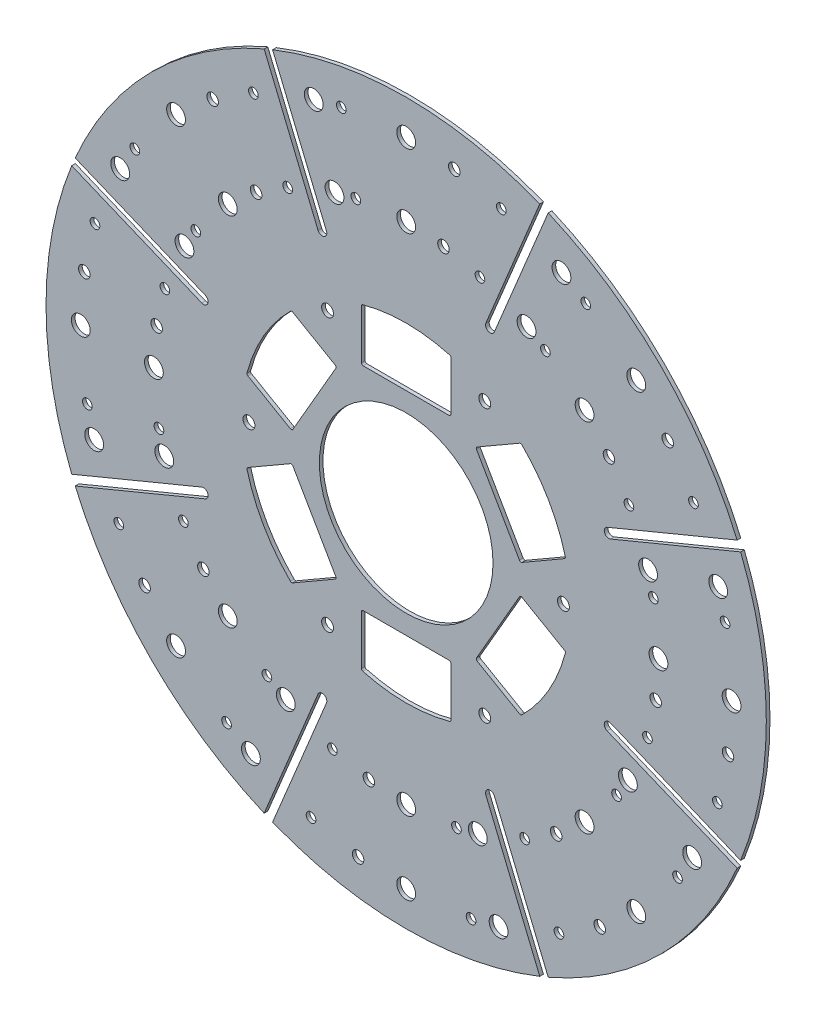
SolidWorks part; units mm, degrees
ref_plane "Plano frontal" through (0, 0, 0) normal (0, 0, 1) x (1, 0, 0)
ref_plane "Plano superior" through (0, 0, 0) normal (0, 1, 0) x (1, 0, 0)
ref_plane "Plano direito" through (0, 0, 0) normal (1, 0, 0) x (0, 0, -1)
sketch "Esboço1" plane through (0, 0, 0) normal (0, 0, 1) x (1, 0, 0)
  circle A0 centre (0, 0) radius 197
  circle A1 centre (0, 0) radius 47.5
  dimension "D1" = 394
  dimension "D2" = 95
extrude "Ressalto-extrusão1" add sketch "Esboço1" along normal blind 2
sketch "Esboço2" plane through (0, 0, 2) normal (0, 0, 1) x (1, 0, 0)
  line L0 (73.0789, 182.961) -> (77.6983, 181.0476)
  line L4 (73.0789, 182.961) -> (43.6023, 111.7982)
  line L5 (77.6983, 181.0476) -> (48.2217, 109.8848)
  line L9 (181.0476, 77.6983) -> (182.961, 73.0789)
  line L10 (181.0476, 77.6983) -> (109.8848, 48.2217)
  line L11 (182.961, 73.0789) -> (111.7982, 43.6023)
  line L15 (182.961, -73.0789) -> (181.0476, -77.6983)
  line L16 (182.961, -73.0789) -> (111.7982, -43.6023)
  line L17 (181.0476, -77.6983) -> (109.8848, -48.2217)
  line L21 (77.6983, -181.0476) -> (73.0789, -182.961)
  line L22 (77.6983, -181.0476) -> (48.2217, -109.8848)
  line L23 (73.0789, -182.961) -> (43.6023, -111.7982)
  line L27 (-73.0789, -182.961) -> (-77.6983, -181.0476)
  line L28 (-73.0789, -182.961) -> (-43.6023, -111.7982)
  line L29 (-77.6983, -181.0476) -> (-48.2217, -109.8848)
  line L33 (-181.0476, -77.6983) -> (-182.961, -73.0789)
  line L34 (-181.0476, -77.6983) -> (-109.8848, -48.2217)
  line L35 (-182.961, -73.0789) -> (-111.7982, -43.6023)
  line L39 (-182.961, 73.0789) -> (-181.0476, 77.6983)
  line L40 (-182.961, 73.0789) -> (-111.7982, 43.6023)
  line L41 (-181.0476, 77.6983) -> (-109.8848, 48.2217)
  line L45 (-77.6983, 181.0476) -> (-73.0789, 182.961)
  line L46 (-77.6983, 181.0476) -> (-48.2217, 109.8848)
  line L47 (-73.0789, 182.961) -> (-43.6023, 111.7982)
  arc A1 (43.6023, 111.7982) -> (48.2217, 109.8848) centre (45.912, 110.8415) ccw
  arc A4 (109.8848, 48.2217) -> (111.7982, 43.6023) centre (110.8415, 45.912) ccw
  arc A6 (111.7982, -43.6023) -> (109.8848, -48.2217) centre (110.8415, -45.912) ccw
  arc A8 (48.2217, -109.8848) -> (43.6023, -111.7982) centre (45.912, -110.8415) ccw
  arc A10 (-43.6023, -111.7982) -> (-48.2217, -109.8848) centre (-45.912, -110.8415) ccw
  arc A12 (-109.8848, -48.2217) -> (-111.7982, -43.6023) centre (-110.8415, -45.912) ccw
  arc A14 (-111.7982, 43.6023) -> (-109.8848, 48.2217) centre (-110.8415, 45.912) ccw
  arc A16 (-48.2217, 109.8848) -> (-43.6023, 111.7982) centre (-45.912, 110.8415) ccw
  point P84 (0, 0)
extrude "Corte-extrusão1" cut sketch "Esboço2" against normal blind 2
sketch "Esboço3" plane through (0, 0, 2) normal (0, 0, 1) x (1, 0, 0)
  line L0 (0, 0) -> (0, 197) construction
  line L1 (0, 0) -> (-35.4875, 174.4266) construction
  line L2 (0, 0) -> (-50.5547, 170.6699) construction
  line L3 (0, 0) -> (26.3101, 176.0448) construction
  line L4 (0, 0) -> (52.0422, 170.2222) construction
  arc A0 (73.0729, 182.9463) -> (-73.0729, 182.9463) centre (0, 0) ccw construction
  circle A1 centre (0, 0) radius 178 construction
  circle A2 centre (0, 0) radius 138 construction
  circle A3 centre (-50.5547, 170.6699) radius 5.15
  circle A4 centre (-39.1941, 132.3171) radius 5.15
  circle A5 centre (-35.4875, 174.4266) radius 2.65
  circle A6 centre (-27.5128, 135.2296) radius 2.65
  circle A7 centre (0, 178) radius 5.15
  circle A8 centre (0, 138) radius 5.15
  circle A9 centre (26.3101, 176.0448) radius 3.15
  circle A10 centre (20.3977, 136.4842) radius 3.15
  circle A11 centre (52.0422, 170.2222) radius 2.65
  circle A12 centre (40.3473, 131.9701) radius 2.65
  circle A13 centre (84.9343, 156.4294) radius 5.15
  circle A14 centre (65.8479, 121.2768) radius 5.15
  circle A15 centre (98.2448, 148.4317) radius 2.65
  circle A16 centre (76.1673, 115.0762) radius 2.65
  circle A17 centre (125.865, 125.865) radius 5.15
  circle A18 centre (97.5807, 97.5807) radius 5.15
  circle A19 centre (143.0865, 105.8785) radius 3.15
  circle A20 centre (110.9322, 82.0855) radius 3.15
  circle A21 centre (157.1647, 83.5659) radius 2.65
  circle A22 centre (121.8468, 64.7871) radius 2.65
  circle A23 centre (170.6699, 50.5547) radius 5.15
  circle A24 centre (132.3171, 39.1941) radius 5.15
  circle A25 centre (174.4266, 35.4875) radius 2.65
  circle A26 centre (135.2296, 27.5128) radius 2.65
  circle A27 centre (178, 0) radius 5.15
  circle A28 centre (138, 0) radius 5.15
  circle A29 centre (176.0448, -26.3101) radius 3.15
  circle A30 centre (136.4842, -20.3977) radius 3.15
  circle A31 centre (170.2222, -52.0422) radius 2.65
  circle A32 centre (131.9701, -40.3473) radius 2.65
  circle A33 centre (156.4294, -84.9343) radius 5.15
  circle A34 centre (121.2768, -65.8479) radius 5.15
  circle A35 centre (148.4317, -98.2448) radius 2.65
  circle A36 centre (115.0762, -76.1673) radius 2.65
  circle A37 centre (125.865, -125.865) radius 5.15
  circle A38 centre (97.5807, -97.5807) radius 5.15
  circle A39 centre (105.8785, -143.0865) radius 3.15
  circle A40 centre (82.0855, -110.9322) radius 3.15
  circle A41 centre (83.5659, -157.1647) radius 2.65
  circle A42 centre (64.7871, -121.8468) radius 2.65
  circle A43 centre (50.5547, -170.6699) radius 5.15
  circle A44 centre (39.1941, -132.3171) radius 5.15
  circle A45 centre (35.4875, -174.4266) radius 2.65
  circle A46 centre (27.5128, -135.2296) radius 2.65
  circle A47 centre (0, -178) radius 5.15
  circle A48 centre (0, -138) radius 5.15
  circle A49 centre (-26.3101, -176.0448) radius 3.15
  circle A50 centre (-20.3977, -136.4842) radius 3.15
  circle A51 centre (-52.0422, -170.2222) radius 2.65
  circle A52 centre (-40.3473, -131.9701) radius 2.65
  circle A53 centre (-84.9343, -156.4294) radius 5.15
  circle A54 centre (-65.8479, -121.2768) radius 5.15
  circle A55 centre (-98.2448, -148.4317) radius 2.65
  circle A56 centre (-76.1673, -115.0762) radius 2.65
  circle A57 centre (-125.865, -125.865) radius 5.15
  circle A58 centre (-97.5807, -97.5807) radius 5.15
  circle A59 centre (-143.0865, -105.8785) radius 3.15
  circle A60 centre (-110.9322, -82.0855) radius 3.15
  circle A61 centre (-157.1647, -83.5659) radius 2.65
  circle A62 centre (-121.8468, -64.7871) radius 2.65
  circle A63 centre (-170.6699, -50.5547) radius 5.15
  circle A64 centre (-132.3171, -39.1941) radius 5.15
  circle A65 centre (-174.4266, -35.4875) radius 2.65
  circle A66 centre (-135.2296, -27.5128) radius 2.65
  circle A67 centre (-178, 0) radius 5.15
  circle A68 centre (-138, 0) radius 5.15
  circle A69 centre (-176.0448, 26.3101) radius 3.15
  circle A70 centre (-136.4842, 20.3977) radius 3.15
  circle A71 centre (-170.2222, 52.0422) radius 2.65
  circle A72 centre (-131.9701, 40.3473) radius 2.65
  circle A73 centre (-156.4294, 84.9343) radius 5.15
  circle A74 centre (-121.2768, 65.8479) radius 5.15
  circle A75 centre (-148.4317, 98.2448) radius 2.65
  circle A76 centre (-115.0762, 76.1673) radius 2.65
  circle A77 centre (-125.865, 125.865) radius 5.15
  circle A78 centre (-97.5807, 97.5807) radius 5.15
  circle A79 centre (-105.8785, 143.0865) radius 3.15
  circle A80 centre (-82.0855, 110.9322) radius 3.15
  circle A81 centre (-83.5659, 157.1647) radius 2.65
  circle A82 centre (-64.7871, 121.8468) radius 2.65
  point P171 (0, 0)
  dimension "D1" = 11.5
  dimension "D5" = 10.3
  dimension "D6" = 5.3
  dimension "D7" = 6.3
  dimension "D2" = 5
  dimension "D3" = 8.5
  dimension "D4" = 8.5
extrude "Corte-extrusão2" cut sketch "Esboço3" against normal blind 2
sketch "Esboço4" plane through (0, 0, 2) normal (0, 0, 1) x (1, 0, 0)
  line L0 (37.9795, 50.2176) -> (62.4795, 7.7824)
  line L1 (-24.5, 58) -> (24.5, 58)
  line L2 (-24.5, 58) -> (-24.5, 86.6011)
  line L3 (24.5, 58) -> (24.5, 86.6011)
  line L4 (37.9795, 50.2176) -> (62.7487, 64.5182)
  line L5 (62.4795, 7.7824) -> (87.2487, 22.0829)
  line L6 (62.4795, -7.7824) -> (37.9795, -50.2176)
  line L7 (62.4795, -7.7824) -> (87.2487, -22.0829)
  line L8 (37.9795, -50.2176) -> (62.7487, -64.5182)
  line L9 (24.5, -58) -> (-24.5, -58)
  line L10 (24.5, -58) -> (24.5, -86.6011)
  line L11 (-24.5, -58) -> (-24.5, -86.6011)
  line L12 (-37.9795, -50.2176) -> (-62.4795, -7.7824)
  line L13 (-37.9795, -50.2176) -> (-62.7487, -64.5182)
  line L14 (-62.4795, -7.7824) -> (-87.2487, -22.0829)
  line L15 (-62.4795, 7.7824) -> (-37.9795, 50.2176)
  line L16 (-62.4795, 7.7824) -> (-87.2487, 22.0829)
  line L17 (-37.9795, 50.2176) -> (-62.7487, 64.5182)
  arc A0 (62.7487, 64.5182) -> (87.2487, 22.0829) centre (0, 0) cw
  arc A1 (-24.5, 86.6011) -> (24.5, 86.6011) centre (0, 0) cw
  arc A2 (87.2487, -22.0829) -> (62.7487, -64.5182) centre (0, 0) cw
  arc A3 (24.5, -86.6011) -> (-24.5, -86.6011) centre (0, 0) cw
  arc A4 (-62.7487, -64.5182) -> (-87.2487, -22.0829) centre (0, 0) cw
  arc A5 (-87.2487, 22.0829) -> (-62.7487, 64.5182) centre (0, 0) cw
  point P28 (0, 0)
extrude "Corte-extrusão3" cut sketch "Esboço4" against normal blind 2
sketch "Esboço5" plane through (0, 0, 2) normal (0, 0, 1) x (1, 0, 0)
  circle A0 centre (0, 0) radius 86 construction
  circle A2 centre (43, 74.4782) radius 3.25
  circle A4 centre (86, 0) radius 3.25
  circle A6 centre (43, -74.4782) radius 3.25
  circle A8 centre (-43, -74.4782) radius 3.25
  circle A10 centre (-86, 0) radius 3.25
  circle A12 centre (-43, 74.4782) radius 3.25
  point P29 (0, 0)
extrude "Corte-extrusão4" cut sketch "Esboço5" against normal blind 2
fillet "Filete1" radius 1 24 edges at (-87.2487, 22.0829, 1) (-62.4795, 7.7824, 1) (-37.9795, 50.2176, 1) (-62.7487, 64.5182, 1) (-62.7487, -64.5182, 1) (-37.9795, -50.2176, 1) (-87.2487, -22.0829, 1) (-62.4795, -7.7824, 1) (-24.5, -86.6011, 1) (24.5, -86.6011, 1) (24.5, -58, 1) (-24.5, -58, 1) (87.2487, -22.0829, 1) (62.7487, -64.5182, 1) (37.9795, -50.2176, 1) (62.4795, -7.7824, 1) (62.4795, 7.7824, 1) (87.2487, 22.0829, 1) (37.9795, 50.2176, 1) (62.7487, 64.5182, 1) (24.5, 86.6011, 1) (24.5, 58, 1) (-24.5, 58, 1) (-24.5, 86.6011, 1)
